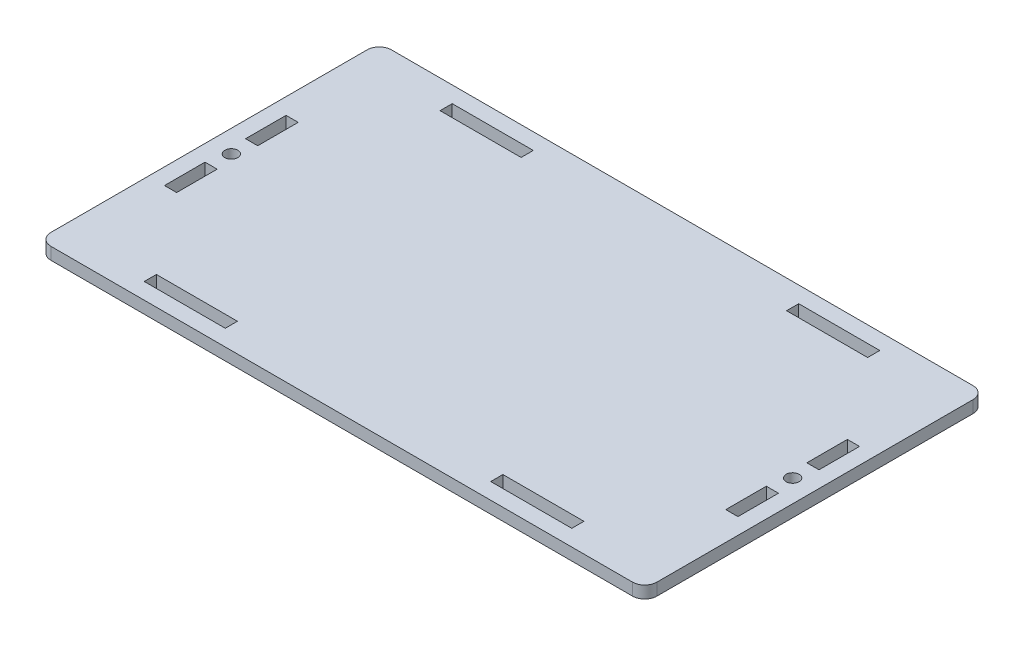
SolidWorks part; units mm, degrees
ref_plane "Спереди" through (0, 0, 0) normal (0, 0, 1) x (1, 0, 0)
ref_plane "Сверху" through (0, 0, 0) normal (0, 1, 0) x (1, 0, 0)
ref_plane "Справа" through (0, 0, 0) normal (1, 0, 0) x (0, 0, -1)
sketch "Sketch1" plane through (0, 0, 0) normal (0, 1, 0) x (1, 0, 0)
  line L0 (27.0121, -43.6459) -> (30.0121, -43.6459) construction
  line L1 (-115.4879, 40.3541) -> (34.0121, 40.3541)
  line L2 (-115.4879, 40.3541) -> (-115.4879, -43.6459)
  line L3 (-115.4879, -43.6459) -> (34.0121, -43.6459)
  line L4 (34.0121, 40.3541) -> (34.0121, -43.6459)
  line L7 (-111.4879, 40.3541) -> (-111.4879, 13.3541) construction
  point P6 (-120.8477, 40.3541)
  dimension "D1" = 4
extrude "Boss-Extrude1" add sketch "Sketch1" along normal blind 3
sketch "Sketch2" plane through (0, 0, 0) normal (0, -1, 0) x (1, 0, 0)
  line L0 (-7.9879, -36.3541) -> (12.0121, -36.3541) construction
  line L1 (12.0121, -36.3541) -> (12.0121, -33.3541) construction
  line L2 (12.0121, -33.3541) -> (-7.9879, -33.3541) construction
  line L3 (-7.9879, -33.3541) -> (-7.9879, -36.3541) construction
  line L4 (-93.4879, -36.3541) -> (-73.4879, -36.3541) construction
  line L5 (-73.4879, -36.3541) -> (-73.4879, -33.3541) construction
  line L6 (-73.4879, -33.3541) -> (-93.4879, -33.3541) construction
  line L7 (-93.4879, -33.3541) -> (-93.4879, -36.3541) construction
  line L8 (-93.4879, 36.6459) -> (-73.4879, 36.6459) construction
  line L9 (-73.4879, 36.6459) -> (-73.4879, 39.6459) construction
  line L10 (-73.4879, 39.6459) -> (-93.4879, 39.6459) construction
  line L11 (-93.4879, 39.6459) -> (-93.4879, 36.6459) construction
  line L12 (-7.9879, 36.6459) -> (12.0121, 36.6459) construction
  line L13 (12.0121, 36.6459) -> (12.0121, 39.6459) construction
  line L14 (12.0121, 39.6459) -> (-7.9879, 39.6459) construction
  line L15 (-7.9879, 39.6459) -> (-7.9879, 36.6459) construction
  line L16 (-7.9879, -36.3541) -> (12.0121, -36.3541)
  line L17 (12.0121, -36.3541) -> (12.0121, -33.3541)
  line L18 (12.0121, -33.3541) -> (-7.9879, -33.3541)
  line L19 (-7.9879, -33.3541) -> (-7.9879, -36.3541)
  line L20 (-93.4879, -36.3541) -> (-73.4879, -36.3541)
  line L21 (-73.4879, -36.3541) -> (-73.4879, -33.3541)
  line L22 (-73.4879, -33.3541) -> (-93.4879, -33.3541)
  line L23 (-93.4879, -33.3541) -> (-93.4879, -36.3541)
  line L24 (-93.4879, 36.6459) -> (-73.4879, 36.6459)
  line L25 (-73.4879, 36.6459) -> (-73.4879, 39.6459)
  line L26 (-73.4879, 39.6459) -> (-93.4879, 39.6459)
  line L27 (-93.4879, 39.6459) -> (-93.4879, 36.6459)
  line L28 (-7.9879, 36.6459) -> (12.0121, 36.6459)
  line L29 (12.0121, 36.6459) -> (12.0121, 39.6459)
  line L30 (12.0121, 39.6459) -> (-7.9879, 39.6459)
  line L31 (-7.9879, 39.6459) -> (-7.9879, 36.6459)
  line L32 (-111.4879, 16.6459) -> (-111.4879, 6.6459) construction
  line L33 (-111.4879, 6.6459) -> (-108.4879, 6.6459) construction
  line L34 (-108.4879, 6.6459) -> (-108.4879, 16.6459) construction
  line L35 (-108.4879, 16.6459) -> (-111.4879, 16.6459) construction
  line L36 (-108.4879, -3.3541) -> (-111.4879, -3.3541) construction
  line L37 (-111.4879, -3.3541) -> (-111.4879, -13.3541) construction
  line L38 (-111.4879, -13.3541) -> (-108.4879, -13.3541) construction
  line L39 (-108.4879, -13.3541) -> (-108.4879, -3.3541) construction
  line L40 (27.0121, 6.6459) -> (30.0121, 6.6459) construction
  line L41 (30.0121, 6.6459) -> (30.0121, 16.6459) construction
  line L42 (30.0121, 16.6459) -> (27.0121, 16.6459) construction
  line L43 (27.0121, 16.6459) -> (27.0121, 6.6459) construction
  line L44 (30.0121, -13.3541) -> (30.0121, -3.3541) construction
  line L45 (30.0121, -3.3541) -> (27.0121, -3.3541) construction
  line L46 (27.0121, -3.3541) -> (27.0121, -13.3541) construction
  line L47 (27.0121, -13.3541) -> (30.0121, -13.3541) construction
  line L48 (-111.4879, 16.6459) -> (-111.4879, 6.6459)
  line L49 (-111.4879, 6.6459) -> (-108.4879, 6.6459)
  line L50 (-108.4879, 6.6459) -> (-108.4879, 16.6459)
  line L51 (-108.4879, 16.6459) -> (-111.4879, 16.6459)
  line L52 (-108.4879, -3.3541) -> (-111.4879, -3.3541)
  line L53 (-111.4879, -3.3541) -> (-111.4879, -13.3541)
  line L54 (-111.4879, -13.3541) -> (-108.4879, -13.3541)
  line L55 (-108.4879, -13.3541) -> (-108.4879, -3.3541)
  line L56 (27.0121, 6.6459) -> (30.0121, 6.6459)
  line L57 (30.0121, 6.6459) -> (30.0121, 16.6459)
  line L58 (30.0121, 16.6459) -> (27.0121, 16.6459)
  line L59 (27.0121, 16.6459) -> (27.0121, 6.6459)
  line L60 (30.0121, -13.3541) -> (30.0121, -3.3541)
  line L61 (30.0121, -3.3541) -> (27.0121, -3.3541)
  line L62 (27.0121, -3.3541) -> (27.0121, -13.3541)
  line L63 (27.0121, -13.3541) -> (30.0121, -13.3541)
extrude "Cut-Extrude1" cut sketch "Sketch2" against normal through all
sketch "Sketch3" plane through (0, 0, 0) normal (0, -1, 0) x (1, 0, 0)
  line L0 (30.0121, -3.3541) -> (27.0121, -3.3541) construction
  line L1 (-108.4879, -3.3541) -> (-111.4879, -3.3541) construction
  line L2 (34.0121, 43.6459) -> (34.0121, -40.3541) construction
  circle A0 centre (28.5121, 1.6459) radius 1.6
  circle A1 centre (-109.9879, 1.6459) radius 1.6
  point P4 (0, 0)
  point P7 (28.5121, -3.3541)
  point P8 (0, 0)
  point P11 (-109.9879, -3.3541)
  point P12 (0, 0)
  point P15 (34.0121, 1.6459)
  dimension "D1" = 3.2
extrude "Cut-Extrude2" cut sketch "Sketch3" against normal through all
fillet "Fillet1" radius 3 4 edges at (-115.4879, 1.5, 43.6459) (-115.4879, 1.5, -40.3541) (34.0121, 1.5, 43.6459) (34.0121, 1.5, -40.3541)
